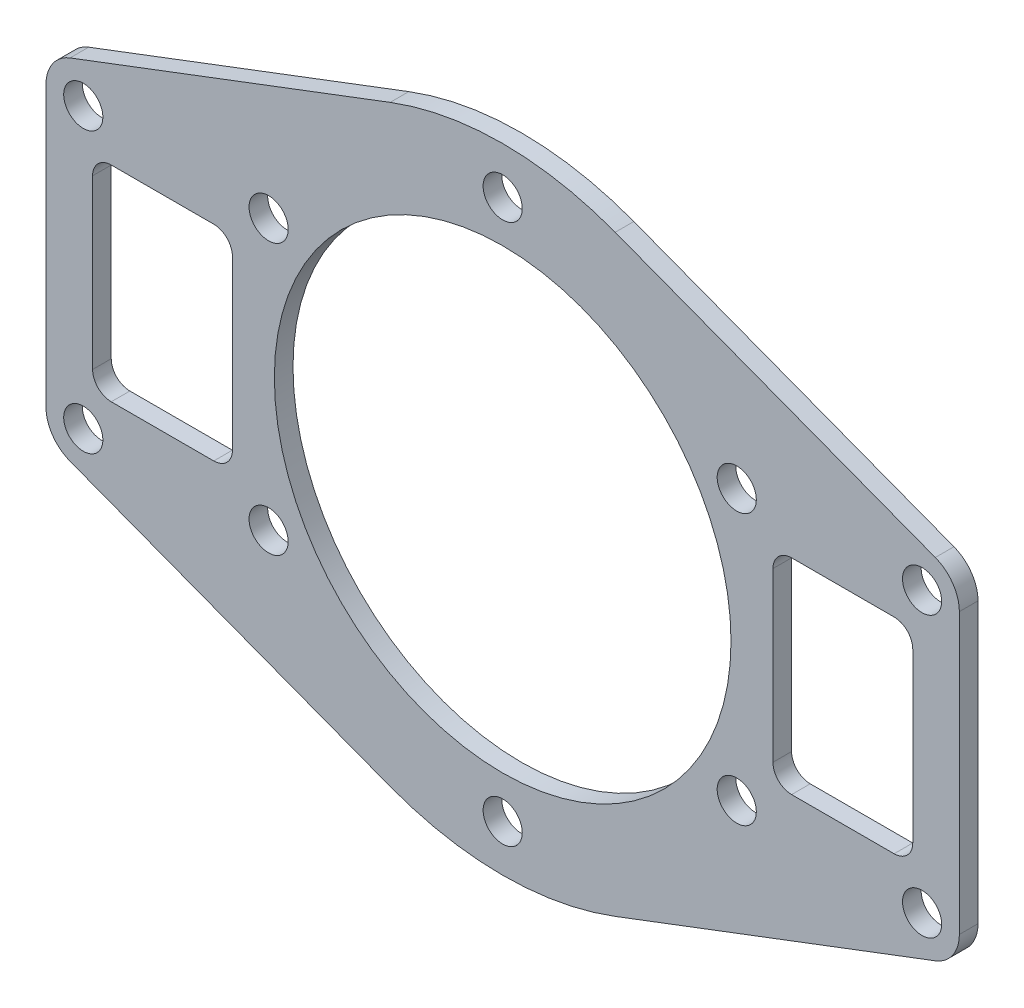
SolidWorks part; units mm, degrees
material "Thornel Mat VMA"
ref_plane "前视基准面" through (0, 0, 0) normal (0, 0, 1) x (1, 0, 0)
ref_plane "上视基准面" through (0, 0, 0) normal (0, 1, 0) x (1, 0, 0)
ref_plane "右视基准面" through (0, 0, 0) normal (1, 0, 0) x (0, 0, -1)
sketch "草图1" plane through (0, 0, 0) normal (0, 0, 1) x (1, 0, 0)
  line L0 (-49, 15) -> (-49, -15)
  line L1 (45, -15) -> (-45, -15) construction
  line L2 (45, -15) -> (45, 15) construction
  line L3 (45, 15) -> (-45, 15) construction
  line L4 (-45, -15) -> (-45, 15) construction
  line L5 (45, -15) -> (-45, 15) construction
  line L6 (45, 15) -> (-45, -15) construction
  line L7 (-46.4202, -18.7394) -> (-12.0717, -31.7848)
  line L8 (12.0717, -31.7848) -> (46.4202, -18.7394)
  line L9 (49, -15) -> (49, 15)
  line L10 (46.4202, 18.7394) -> (12.0717, 31.7848)
  line L11 (-12.0717, 31.7848) -> (-46.4202, 18.7394)
  circle A0 centre (0, 0) radius 24.5
  circle A1 centre (0, 0) radius 29 construction
  circle A2 centre (0, 29) radius 2.1
  circle A3 centre (25.1147, 14.5) radius 2.1
  circle A4 centre (25.1147, -14.5) radius 2.1
  circle A5 centre (0, -29) radius 2.1
  circle A6 centre (-25.1147, -14.5) radius 2.1
  circle A7 centre (-25.1147, 14.5) radius 2.1
  circle A8 centre (-45, 15) radius 2.1
  circle A9 centre (-45, -15) radius 2.1
  circle A10 centre (45, -15) radius 2.1
  circle A11 centre (45, 15) radius 2.1
  arc A12 (-12.0717, -31.7848) -> (12.0717, -31.7848) centre (0, 0) ccw
  arc A13 (12.0717, 31.7848) -> (-12.0717, 31.7848) centre (0, 0) ccw
  arc A14 (49, 15) -> (46.4202, 18.7394) centre (45, 15) ccw
  arc A15 (46.4202, -18.7394) -> (49, -15) centre (45, -15) ccw
  arc A16 (-49, -15) -> (-46.4202, -18.7394) centre (-45, -15) ccw
  arc A17 (-49, 15) -> (-46.4202, 18.7394) centre (-45, 15) cw
  point P18 (0, 0)
  dimension "D1" = 49
  dimension "D2" = 58
  dimension "D3" = 4.2
  dimension "D5" = 4.2
  dimension "D8" = 34
  dimension "D9" = 4
  dimension "D6" = 30
  dimension "D7" = 90
  dimension "D4" = 6
extrude "凸台-拉伸1" add sketch "草图1" along normal blind 2
sketch "草图2" plane through (0, 0, 2) normal (0, 0, 1) x (1, 0, 0)
  line L0 (29, 0) -> (-29, 0) construction
  line L1 (-42, 11) -> (-31, 11)
  line L2 (-44, 9) -> (-44, -9)
  line L3 (-42, -11) -> (-31, -11)
  line L4 (-29, 9) -> (-29, -9)
  line L5 (31, 11) -> (42, 11)
  line L6 (29, 9) -> (29, -9)
  line L7 (31, -11) -> (42, -11)
  line L8 (44, 9) -> (44, -9)
  line L9 (-49, 15) -> (-49, -15) construction
  arc A0 (42, 11) -> (44, 9) centre (42, 9) cw
  arc A1 (29, -9) -> (31, -11) centre (31, -9) ccw
  arc A2 (42, -11) -> (44, -9) centre (42, -9) ccw
  arc A3 (31, 11) -> (29, 9) centre (31, 9) ccw
  arc A4 (-31, 11) -> (-29, 9) centre (-31, 9) cw
  arc A5 (-44, -9) -> (-42, -11) centre (-42, -9) ccw
  arc A6 (-31, -11) -> (-29, -9) centre (-31, -9) ccw
  arc A7 (-42, 11) -> (-44, 9) centre (-42, 9) ccw
  point P25 (-44, -11)
  point P30 (-44, 11)
  dimension "D4" = 2
  dimension "D5" = 2
  dimension "D1" = 58
  dimension "D2" = 5
  dimension "D3" = 22
extrude "切除-拉伸1" cut sketch "草图2" against normal blind 10
